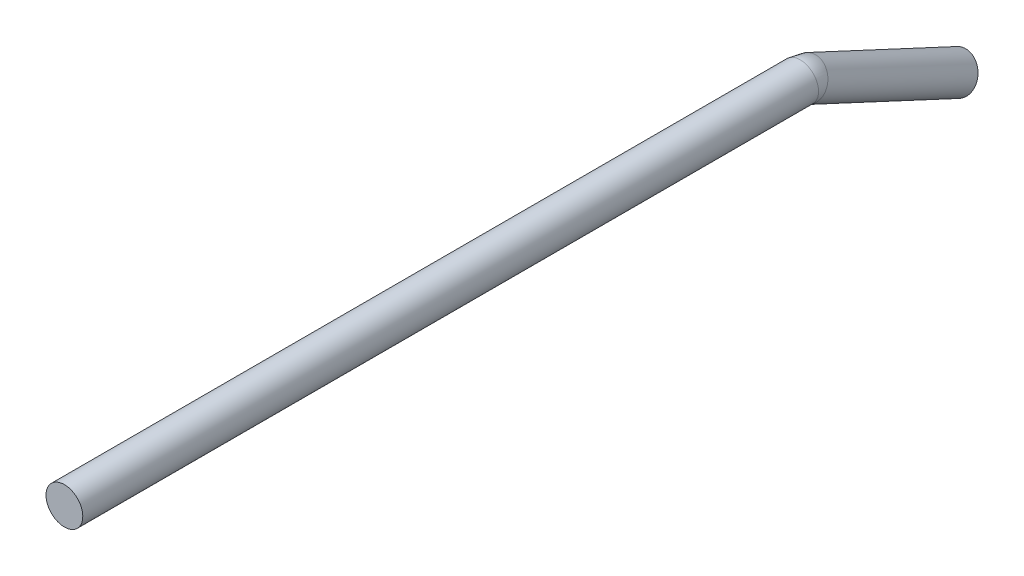
SolidWorks part; units mm, degrees
ref_plane "Front Plane" through (0, 0, 0) normal (0, 0, 1) x (1, 0, 0)
ref_plane "Top Plane" through (0, 0, 0) normal (0, 1, 0) x (1, 0, 0)
ref_plane "Right Plane" through (0, 0, 0) normal (1, 0, 0) x (0, 0, -1)
sketch "Sketch1" plane through (0, 0, 0) normal (0, 1, 0) x (1, 0, 0)
  circle A0 centre (0, 0) radius 12.5
  dimension "D1" = 25
extrude "Boss-Extrude1" [suppressed] add sketch "Sketch1" along normal mid plane 500
sketch "Sketch2" [suppressed] plane through (0, 0, 0) normal (0, 0, 1) x (1, 0, 0)
  line L0 (-46.307, 245) -> (67.1241, 245)
  line L1 (12.5, 250) -> (-12.5, 250) construction
  line L2 (-46.307, 245) -> (-46.307, 145)
  line L3 (-46.307, 145) -> (58.77, 145)
  dimension "D1" = 5
  dimension "D2" = 100
split line "Split Line1" [suppressed]
chamfer "Chamfer1" [suppressed] distance 2 angle 45
sketch "Sketch3" [suppressed] plane through (0, -250, 0) normal (0, -1, 0) x (1, 0, 0)
  circle A0 centre (0, 0) radius 12.5
  circle A1 centre (0, 0) radius 10
extrude "Cut-Extrude1" [suppressed] cut sketch "Sketch3" against normal blind 20
sketch "Sketch4" plane through (0, 0, 0) normal (1, 0, 0) x (0, 0, -1)
  line L0 (-2.2123, 0) -> (-402.2123, 0)
  line L1 (2.0059, -0.9332) -> (83.607, -38.8972)
  arc A0 (-2.2123, 0) -> (2.0059, -0.9332) centre (-2.2123, -10) cw
  point P8 (0, 0)
  dimension "D1" = 10
  dimension "D2" = 400
  dimension "D3" = 90
sketch "Sketch5" plane through (0, 0, 0) normal (0, 0, 1) x (1, 0, 0)
  circle A0 centre (0, 0) radius 12.5
sweep "Sweep3" add path "Sketch4" circular profile diameter 20 parameters "D3"=20
equation "\"Bar-Diameter\"= 25"
